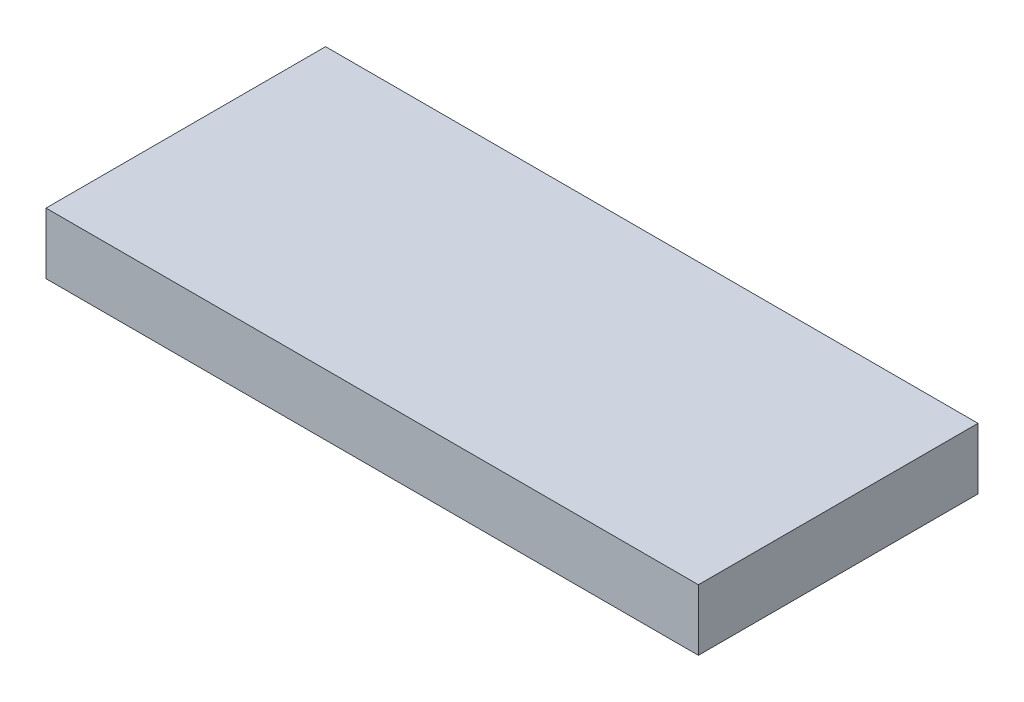
SolidWorks part; units mm, degrees
ref_plane "前基準面" through (0, 0, 0) normal (0, 0, 1) x (1, 0, 0)
ref_plane "上基準面" through (0, 0, 0) normal (0, 1, 0) x (1, 0, 0)
ref_plane "右基準面" through (0, 0, 0) normal (1, 0, 0) x (0, 0, -1)
sketch "草圖1" plane through (0, 0, 0) normal (0, 1, 0) x (1, 0, 0)
  line L1 (-26.67, -11.43) -> (26.67, -11.43)
  line L2 (-26.67, -11.43) -> (-26.67, 11.43)
  line L3 (-26.67, 11.43) -> (26.67, 11.43)
  line L4 (26.67, -11.43) -> (26.67, 11.43)
  line L5 (-26.67, -11.43) -> (26.67, 11.43) construction
  line L6 (-26.67, 11.43) -> (26.67, -11.43) construction
  point P0 (0, 0)
  dimension "D1" = 53.34
  dimension "D2" = 22.86
extrude "填料-伸長1" add sketch "草圖1" along normal blind 5
